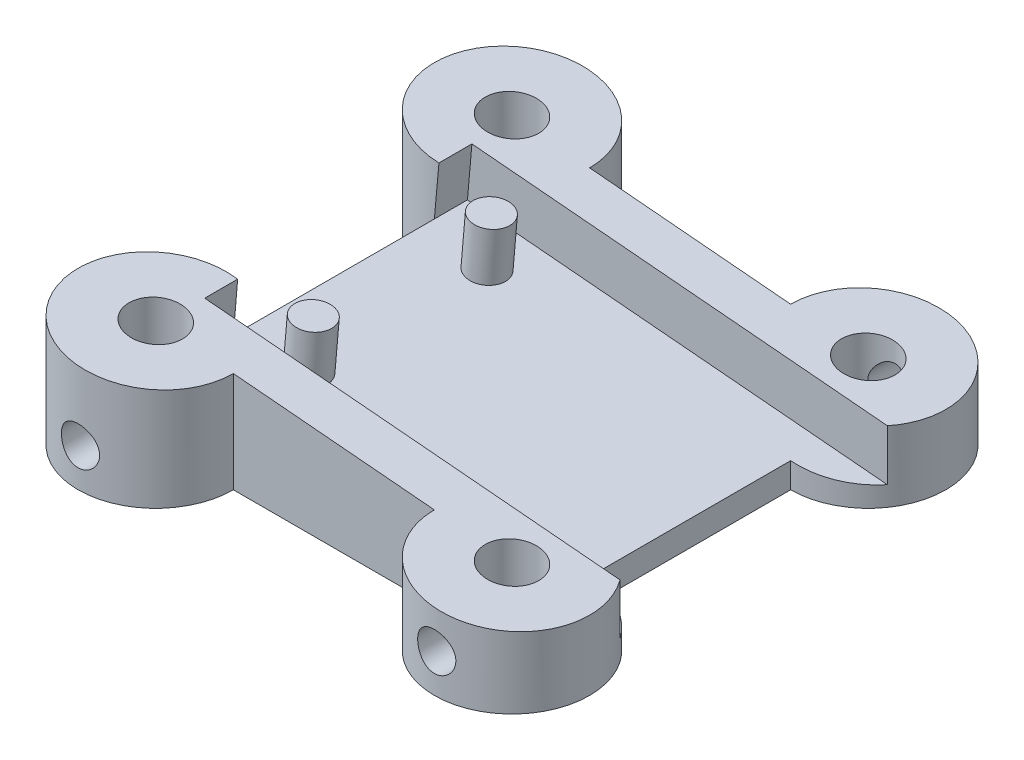
SolidWorks part; units mm, degrees
ref_plane "Front Plane" through (0, 0, 0) normal (0, 0, 1) x (1, 0, 0)
ref_plane "Top Plane" through (0, 0, 0) normal (0, 1, 0) x (1, 0, 0)
ref_plane "Right Plane" through (0, 0, 0) normal (1, 0, 0) x (0, 0, -1)
sketch "Sketch1" plane through (0, 0, 0) normal (0, 1, 0) x (1, 0, 0)
  line L0 (14, 28) -> (14, 0) construction
  line L1 (0, 0) -> (28, 0)
  line L2 (0, 0) -> (0, 28)
  line L3 (0, 28) -> (28, 28)
  line L4 (28, 0) -> (28, 28)
  line L5 (0, 14) -> (28, 14) construction
  point P9 (14, 14)
  dimension "D1" = 28
extrude "Boss-Extrude1" add sketch "Sketch1" along normal blind 8.4497
sketch "Sketch2" plane through (0, 0, 0) normal (0, 0, 1) x (1, 0, 0)
  line L0 (0, 8.4497) -> (28, 6)
  line L1 (0, 8.4497) -> (28, 8.4497) construction
  line L2 (28, 8.4497) -> (28, 0) construction
  line L3 (0, 8.4497) -> (28, 8.4497)
  line L4 (28, 8.4497) -> (28, 6)
  dimension "D2" = 6
  dimension "D3" = 5
extrude "Cut-Extrude1" cut sketch "Sketch2" against normal through all
sketch "Sketch3" plane through (0.7336, 8.3855, 0) normal (0.0872, 0.9962, 0) x (0.9962, -0.0872, 0)
  line L0 (-0.7364, 28) -> (-0.7364, 0) construction
  line L1 (-0.7364, 3.5) -> (49.2636, 3.5)
  line L2 (-0.7364, 3.5) -> (-0.7364, 24.5)
  line L3 (-0.7364, 24.5) -> (49.2636, 24.5)
  line L4 (49.2636, 3.5) -> (49.2636, 24.5)
  point P9 (-0.7364, 14)
  point P10 (-0.7364, 14)
  dimension "D1" = 21
  dimension "D2" = 50
extrude "Cut-Extrude2" cut sketch "Sketch3" against normal blind 4
ref_plane "Plane1" through (0, 8.4497, 0) normal (0, 1, 0) x (1, 0, 0)
sketch "Sketch11" plane through (0.385, 4.4007, 0) normal (0.0872, 0.9962, 0) x (0.9962, -0.0872, 0)
  line L0 (27.7205, 24.5) -> (-0.3865, 24.5) construction
  line L1 (27.7205, 24.5) -> (27.7205, 3.5) construction
  line L2 (-0.3865, 3.5) -> (27.7205, 3.5) construction
  line L3 (27.7205, 24.5) -> (-0.3865, 24.5) construction
  line L4 (27.7205, 24.5) -> (27.7205, 3.5) construction
  line L5 (-0.3865, 3.5) -> (27.7205, 3.5) construction
  line L6 (13.667, 3) -> (13.667, 50003) construction
  line L7 (24.633, 14) -> (-49975.367, 14) construction
  circle A2 centre (4.667, 21) radius 1.45
  circle A3 centre (4.667, 7) radius 1.45
  point P6 (13.667, 3.5)
  point P9 (27.7205, 14)
  dimension "D4" = 2.9
  dimension "D5" = 9
  dimension "D6" = 7
extrude "Boss-Extrude2" add sketch "Sketch11" along normal blind 4
sketch "Sketch12" plane through (0, 8.4497, 0) normal (0, 1, 0) x (1, 0, 0)
  line L0 (0, 3.5) -> (0, 24.5) construction
  line L1 (0, 3.5) -> (28, 3.5) construction
  line L2 (0, 3.5) -> (0, 24.5) construction
  line L3 (0, 3.5) -> (28, 3.5) construction
  line L4 (0, 14) -> (50000, 14) construction
  line L5 (14, 4) -> (14, 50004) construction
  circle A0 centre (14, 14) radius 7
  point P7 (0, 14)
  point P10 (14, 3.5)
  dimension "D1" = 14
sketch "Sketch13" plane through (0, 0, 0) normal (0, -1, 0) x (1, 0, 0)
  line L0 (0, 0) -> (28, 0) construction
  line L1 (28, 0) -> (28, -28) construction
  line L2 (28, -28) -> (0, -28) construction
  line L3 (0, -28) -> (0, 0) construction
  line L4 (0, 0) -> (28, 0) construction
  line L5 (28, 0) -> (28, -28) construction
  line L6 (28, -28) -> (0, -28) construction
  line L7 (0, -28) -> (0, 0) construction
  line L8 (0, -14) -> (28, -14) construction
  line L9 (14, -28) -> (14, 0) construction
  circle A0 centre (0, 0) radius 2.1
  circle A1 centre (28, 0) radius 2.1
  circle A2 centre (28, -28) radius 2.1
  circle A3 centre (0, -28) radius 2.1
  dimension "D1" = 4.2
  dimension "D2" = 2
  dimension "D3" = 2
extrude "Cut-Extrude5" cut sketch "Sketch13" against normal through all
sketch "Sketch14" plane through (0, 0, 0) normal (0, -1, 0) x (1, 0, 0)
  line L0 (28, -3.5) -> (28, -2.1) construction
  line L1 (2.1, -28) -> (25.9, -28) construction
  line L2 (0, -3.5) -> (0, -24.5) construction
  circle A0 centre (0, 0) radius 2.1 construction
  circle A1 centre (0, 0) radius 2.1 construction
  circle A2 centre (0, 0) radius 6.1
  circle A3 centre (0, 0) radius 2.1
  circle A4 centre (28, 0) radius 2.1
  circle A5 centre (28, 0) radius 6.1
  circle A6 centre (28, -28) radius 2.1
  circle A7 centre (28, -28) radius 6.1
  circle A8 centre (0, -28) radius 2.1
  circle A9 centre (0, -28) radius 6.1
  dimension "D1" = 4
  dimension "D4" = 4.2
  dimension "D2" = 2
  dimension "D3" = 2
extrude "Boss-Extrude3" add sketch "Sketch14" against normal up to surface (8.4497 mm away)
sketch "Sketch15" plane through (0, 0, -28) normal (0, 0, -1) x (-1, 0, 0)
  line L0 (-21.9, 0) -> (-6.1, 0) construction
  line L1 (-21.9, 0) -> (-0.9, 0) construction
  line L4 (-14, 7.2248) -> (-14, 0) construction
  line L5 (-6.1, 7.916) -> (-21.9, 6.5337) construction
  circle A0 centre (-28, 3) radius 1.5
  circle A1 centre (0, 3) radius 1.5
  point P4 (-28, 0)
  dimension "D1" = 3
  dimension "D2" = 3
extrude "Cut-Extrude6" cut sketch "Sketch15" along normal through all
sketch "Sketch16" plane through (0, 0, 0) normal (0, 0, 1) x (1, 0, 0)
  circle A0 centre (0, 3) radius 1.5 construction
  circle A1 centre (28, 3) radius 1.5 construction
  circle A2 centre (0, 3) radius 1.5
  circle A3 centre (28, 3) radius 1.5
extrude "Cut-Extrude7" cut sketch "Sketch16" along normal through all
sketch "Sketch18" plane through (0.7336, 8.3855, 0) normal (0.0872, 0.9962, 0) x (0.9962, -0.0872, 0)
  line L5 (-0.7364, 3.5) -> (27.157, 3.5) construction
  line L8 (4.2786, 3.5) -> (22.3554, 3.5) construction
  line L9 (4.2786, 3.5) -> (22.3554, 3.5) construction
  line L22 (4.6286, 24.5) -> (-0.3865, 24.5)
  line L37 (7.3554, 3.5) -> (37.3554, 3.5)
  line L38 (7.3554, 3.5) -> (7.3554, 24.5)
  line L39 (7.3554, 24.5) -> (37.3554, 24.5)
  line L40 (37.3554, 3.5) -> (37.3554, 24.5)
  line L42 (-0.3865, 24.5) -> (-0.3865, 21.9)
  line L46 (-0.3865, 6.1) -> (-0.3865, 3.5)
  line L47 (-0.3865, 3.5) -> (4.6286, 3.5)
  line L49 (4.2786, 24.5) -> (22.3554, 24.5) construction
  ellipse E1 centre (-0.3865, 28) end of major axis (5.7368, 28) minor radius 6.1 (-0.3865, 21.9) -> (4.6286, 24.5) ccw construction
  ellipse E2 centre (-0.3865, 28) end of major axis (5.7368, 28) minor radius 6.1 (-0.3865, 21.9) -> (4.6286, 24.5) ccw
  ellipse E3 centre (-0.3865, 0) end of major axis (5.7368, 0) minor radius 6.1 (4.6286, 3.5) -> (-0.3865, 6.1) ccw construction
  ellipse E4 centre (-0.3865, 0) end of major axis (5.7368, 0) minor radius 6.1 (4.6286, 3.5) -> (-0.3865, 6.1) ccw
  point P7 (22.3554, 3.5)
  dimension "D1" = 30
extrude "Cut-Extrude8" cut sketch "Sketch18" against normal up to surface (4 mm away) up to face at (6.4787, 3.8676, -21)
equation "\"TrackLength\"= 150"
equation "\"MarbleWidth\"= 13"
equation "\"MarbleTrackWidth\"= \"MarbleWidth\" - 1"
equation "\"TrackWidth\"= \"MarbleTrackWidth\" + ( 2 * 4 )"
equation "\"MarbleTrackLength\"= \"TrackLength\" - ( 2 * 8 )"
equation "\"MountWidth\"= \"TrackWidth\" + 8"
equation "\"D1@Sketch1\"=\"MountWidth\""
equation "\"D1@Boss-Extrude1\"=\"RampHeight\""
equation "\"RampDepth\"=6"
equation "\"RampAngle\"= 5"
equation "\"RampHeight\"= ( \"MountWidth\" * tan ( \"RampAngle\" ) ) + \"RampDepth\""
equation "\"D1@Sketch3\"=\"TrackWidth\" + 1"
equation "\"MountWidth\"= \"TrackWidth\" + 10"
equation "\"MountLength\"=66.6651"
